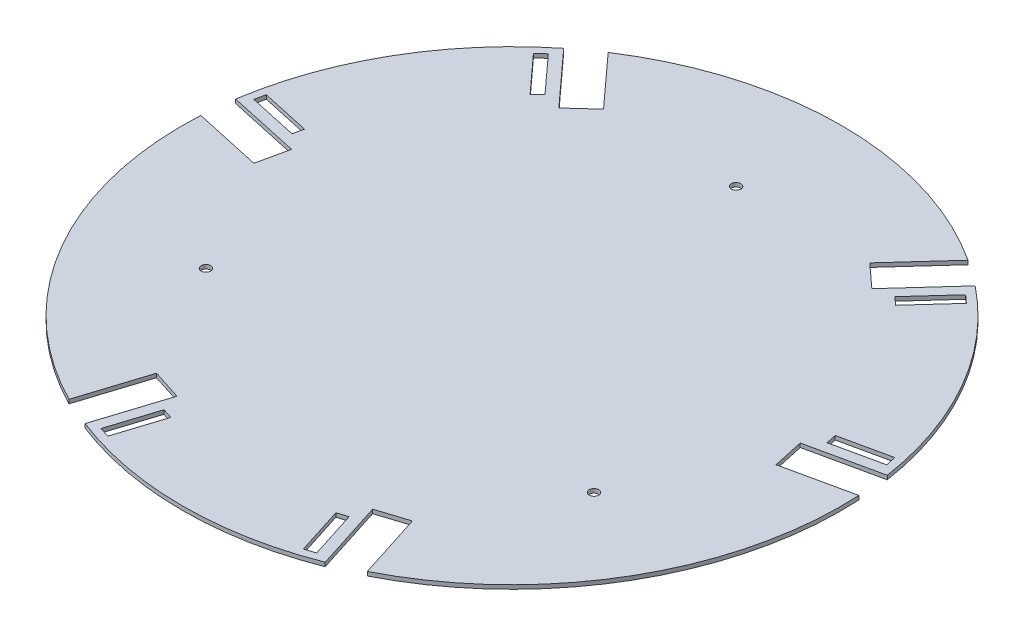
SolidWorks part; units mm, degrees
ref_plane "Front Plane" through (0, 0, 0) normal (0, 0, 1) x (1, 0, 0)
ref_plane "Top Plane" through (0, 0, 0) normal (0, 1, 0) x (1, 0, 0)
ref_plane "Right Plane" through (0, 0, 0) normal (1, 0, 0) x (0, 0, -1)
sketch "Sketch2" plane through (0, 0, 0) normal (0, 1, 0) x (1, 0, 0)
  circle A0 centre (0, 0) radius 125
  dimension "D1" = 250
extrude "Boss-Extrude1" add sketch "Sketch2" along normal blind 1.5 contours A0
sketch "Sketch3" plane through (0, 1.5, 0) normal (0, 1, 0) x (1, 0, 0)
  line L0 (0, 0) -> (-38, -119.084) construction
  line L1 (-270.1917, -358.6733) -> (-267.1917, -358.6733)
  line L2 (-270.1917, -358.6733) -> (-270.1917, -377.6733)
  line L3 (-270.1917, -377.6733) -> (-267.1917, -377.6733)
  line L4 (-267.1917, -358.6733) -> (-267.1917, -377.6733)
  line L9 (-38, -119.084) -> (38, -119.084) construction
  line L10 (0, 0) -> (0, -293.8403) construction
  line L11 (31.312, -98.1252) -> (35.1227, -96.9092)
  line L12 (37.088, -116.226) -> (40.8987, -115.01)
  line L14 (37.088, -116.226) -> (31.312, -98.1252)
  line L15 (40.8987, -115.01) -> (35.1227, -96.9092)
  line L17 (-38, -119.084) -> (-37.088, -116.226) construction
  line L19 (-37.088, -116.226) -> (-31.312, -98.1252)
  line L20 (-37.088, -116.226) -> (-40.8987, -115.01)
  line L21 (-31.312, -98.1252) -> (-35.1227, -96.9092)
  line L22 (-40.8987, -115.01) -> (-35.1227, -96.9092)
  line L52 (-82.1107, 90.2321) -> (-69.3229, 76.1796)
  line L53 (-82.1107, 90.2321) -> (-79.1522, 92.9243)
  line L54 (-79.1522, 92.9243) -> (-66.3645, 78.8717)
  line L55 (-69.3229, 76.1796) -> (-66.3645, 78.8717)
  line L56 (-100.6349, 21.9456) -> (-101.4872, 18.0375)
  line L57 (-120.0509, 22.0857) -> (-101.4872, 18.0375)
  line L58 (-119.1987, 25.9938) -> (-120.0509, 22.0857)
  line L59 (-119.1987, 25.9938) -> (-100.6349, 21.9456)
  line L60 (119.1987, 25.9938) -> (100.6349, 21.9456)
  line L61 (119.1987, 25.9938) -> (120.0509, 22.0857)
  line L62 (120.0509, 22.0857) -> (101.4872, 18.0375)
  line L63 (100.6349, 21.9456) -> (101.4872, 18.0375)
  line L64 (69.3229, 76.1796) -> (66.3645, 78.8717)
  line L65 (79.1522, 92.9243) -> (66.3645, 78.8717)
  line L66 (82.1107, 90.2321) -> (79.1522, 92.9243)
  line L67 (82.1107, 90.2321) -> (69.3229, 76.1796)
  circle A1 centre (0, 0) radius 125 construction
  point P18 (0, 0)
  point P38 (-15.7426, 25.0605)
  point P39 (0, 0)
  point P46 (-7.6333, 12.5317)
  dimension "D1" = 3
  dimension "D2" = 19
  dimension "D3" = 76
  dimension "D4" = 3
  dimension "D5" = 3
  dimension "D7" = 4
  dimension "D8" = 19
extrude "Cut-Extrude1" cut sketch "Sketch3" against normal through all
sketch "Sketch4" plane through (0, 1.5, 0) normal (0, 1, 0) x (1, 0, 0)
  circle A3 centre (0, 85) radius 1.8
  circle A4 centre (73.6122, -42.5) radius 1.8
  circle A5 centre (-73.6122, -42.5) radius 1.8
  point P8 (0, 0)
  dimension "D1" = 85
  dimension "D2" = 3
  dimension "D3" = 3.6
extrude "Cut-Extrude2" cut sketch "Sketch4" against normal through all
sketch "Sketch6" plane through (0, 1.5, 0) normal (0, 1, 0) x (1, 0, 0)
  line L0 (-40.8987, -115.01) -> (-44.7094, -113.794) construction
  line L1 (-35.1227, -96.9092) -> (-40.8987, -115.01) construction
  line L2 (0, 0) -> (0, -140.3527) construction
  line L3 (-44.7094, -113.794) -> (-55.9925, -149.153) construction
  line L4 (-55.9925, -149.153) -> (-67.4246, -145.505)
  line L5 (-55.9925, -149.153) -> (-37.1094, -89.9772)
  line L6 (-67.4246, -145.505) -> (-48.5414, -86.3292)
  line L7 (-37.1094, -89.9772) -> (-48.5414, -86.3292)
  line L8 (67.4246, -145.505) -> (48.5414, -86.3292)
  line L9 (37.1094, -89.9772) -> (48.5414, -86.3292)
  line L10 (55.9925, -149.153) -> (37.1094, -89.9772)
  line L11 (55.9925, -149.153) -> (67.4246, -145.505)
  dimension "D1" = 12
  dimension "D2" = 25
  dimension "D3" = 4
extrude "Cut-Extrude5" cut sketch "Sketch6" against normal through all
pattern_circular "CirPattern2" count 3 over 360 about axis through (0, 0, 0) along (0, 1, 0) of "Cut-Extrude5"
sketch "Sketch7" [suppressed] plane through (0, 1.5, 0) normal (0, 1, 0) x (1, 0, 0)
  line L0 (0, 0) -> (123.5839, 18.7621)
  line L1 (-0.2769, 0.4642) -> (78.0404, 97.6457)
  line L2 (124.8177, 6.7492) -> (-0.2769, 0.4642)
  line L3 (-0.2769, 0.4642) -> (56.5639, -111.4698)
  line L4 (56.5639, -111.4698) -> (48.5414, -86.3292) construction
  line L5 (59.3678, 77.1263) -> (78.0404, 97.6457) construction
  arc A0 (56.5639, -111.4698) -> (124.8177, 6.7492) centre (0, 0) ccw construction
  arc A1 (56.5639, -111.4698) -> (124.8177, 6.7492) centre (0, 0) ccw
  dimension "D2" = 9.224
  dimension "D1" = 65.954
  dimension "D3" = 42.503
  dimension "D4" = 3.437
